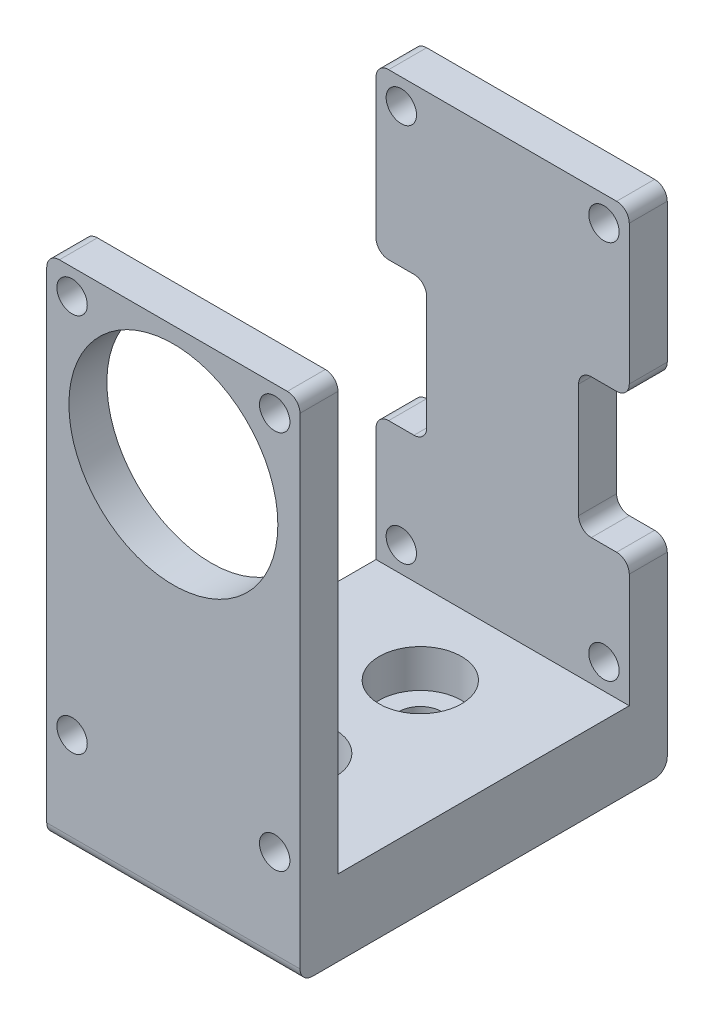
SolidWorks part; units mm, degrees
ref_plane "Front" through (0, 0, 0) normal (0, 0, 1) x (1, 0, 0)
ref_plane "Top" through (0, 0, 0) normal (0, 1, 0) x (1, 0, 0)
ref_plane "Right" through (0, 0, 0) normal (1, 0, 0) x (0, 0, -1)
sketch "Sketch1" plane through (0, 0, 0) normal (1, 0, 0) x (0, 0, -1)
  line L0 (29, 0) -> (29, 40)
  line L2 (3, 6) -> (3, 40)
  line L3 (3, 40) -> (0, 40)
  line L4 (0, 0) -> (0, 40)
  line L5 (0, 0) -> (29, 0)
  line L7 (3, 6) -> (26, 6)
  line L9 (29, 40) -> (26, 40)
  line L10 (26, 40) -> (26, 6)
  line B0 (26, 8) -> (3, 8) construction
  line B1 (26, 40) -> (26, 6) construction
  line B2 (26, 40) -> (3, 40) construction
  line B3 (3, 40) -> (3, 6) construction
  line B4 (26, 6) -> (3, 6) construction
  line B5 (26, 38) -> (3, 38) construction
  line B6 (0, 30.5) -> (29, 30.5) construction
  dimension "D1" = 6
  dimension "D2" = 3
sketch_block_instance "DYNAMIXEL 330 Side-1"
sketch_block "DYNAMIXEL 330 Side" parameters "D1"=30, "D2"=34, "D3"=23, "D4"=2, "D5"=33.2021, "D6"=6.9234, "D7"=26.2787
extrude "Boss-Extrude1" add sketch "Sketch1" along normal mid plane 20 contours L9 L10 L7 L2 L3 L4 L5 L0
sketch "Sketch2" plane through (0, 0, 0) normal (0, 0, 1) x (1, 0, 0)
  line L0 (10, 40) -> (-10, 40) construction
  circle A0 centre (0, 30.5) radius 8.25
  line B0 (10, 40) -> (-10, 40) construction
  line B1 (-10, 40) -> (-10, 6) construction
  line B2 (-10, 6) -> (10, 6) construction
  line B3 (10, 6) -> (10, 40) construction
  dimension "D1" = 16.5
sketch_block_instance "DYNAMIXEL 330 Front-1"
sketch_block "DYNAMIXEL 330 Front" parameters "D1"=34, "D2"=20, "D3"=30, "D4"=16, "D5"=2, "D6"=2, "D7"=9.5, "D8"=10
extrude "Cut-Extrude1" cut sketch "Sketch2" against normal up to next contours A0
hole_wizard "M2 Clearance Hole1" positions "Sketch3" profile "Sketch4" hole size "M2" standard "ANSI Metric" end condition through all
sketch "Sketch3" plane through (0, 0, 0) normal (0, 0, 1) x (1, 0, 0)
  point P0 (-8, 8)
  point P3 (8, 8)
  point P6 (8, 38)
  point P9 (-8, 38)
sketch "Sketch4" plane through (-8, 8, 0) normal (1, 0, 0) x (0, -1, 0)
  line L0 (0, 0) -> (0, 29)
  line L1 (0, 29) -> (1.2, 29)
  line L2 (1.2, 29) -> (1.2, 0)
  line L5 (1.2, 0) -> (0, 0)
  line L11 (0, -6.35) -> (0, 107.95) construction
  dimension "Thru Hole Dia." = 2.4
  dimension "Thru Hole Depth" = 29
hole_wizard "CBORE for M3 SHCS1" positions "Sketch5" profile "Sketch6" counterbore size "M3" standard "ANSI Metric" end condition through all
sketch "Sketch5" plane through (0, 6, 0) normal (0, 1, 0) x (1, 0, 0)
  line L0 (0, 29) -> (0, 19.5) construction
  line L2 (0, 9.5) -> (0, 0) construction
  line L4 (10, 29) -> (-10, 29) construction
  point P0 (0, 19.5)
  point P2 (0, 9.5)
  dimension "D1" = 10
sketch "Sketch6" plane through (0, 6, -19.5) normal (1, 0, 0) x (0, 0, 1)
  line L0 (0, 0) -> (0, 6)
  line L1 (0, 6) -> (1.7, 6)
  line L3 (1.7, 6) -> (1.7, 3)
  line L4 (1.7, 3) -> (3.25, 3)
  line L5 (3.25, 3) -> (3.25, 0)
  line L7 (3.25, 0) -> (0, 0)
  line L11 (0, -6.35) -> (0, 107.95) construction
  dimension "Thru Hole Dia." = 3.4
  dimension "Thru Hole Depth" = 6
  dimension "C'Bore Dia." = 6.5
  dimension "C'Bore Depth" = 3
sketch "Sketch7" plane through (0, 0, -29) normal (0, 0, 1) x (1, 0, 0)
  line L0 (10, 6) -> (10, 40) construction
  line L1 (10, 27) -> (6, 27)
  line L2 (10, 27) -> (10, 16)
  line L3 (10, 16) -> (6, 16)
  line L4 (6, 27) -> (6, 16)
  line L5 (-10, 6) -> (10, 6) construction
  line L6 (0, -50) -> (0, 50) construction
  line L7 (-6, 27) -> (-6, 16)
  line L8 (-10, 16) -> (-6, 16)
  line L9 (-10, 27) -> (-10, 16)
  line L10 (-10, 27) -> (-6, 27)
  dimension "D1" = 11
  dimension "D2" = 4
  dimension "D3" = 10
extrude "Cut-Extrude2" cut sketch "Sketch7" along normal up to next
fillet "Fillet1" radius 1 14 edges at (0, 0, -29) (0, 0, 0) (-10, 40, -1.5) (-10, 40, -27.5) (10, 40, -27.5) (10, 40, -1.5) (6, 27, -27.5) (10, 16, -27.5) (-10, 16, -27.5) (-6, 16, -27.5) (-6, 27, -27.5) (-10, 27, -27.5) (10, 27, -27.5) (6, 16, -27.5)
